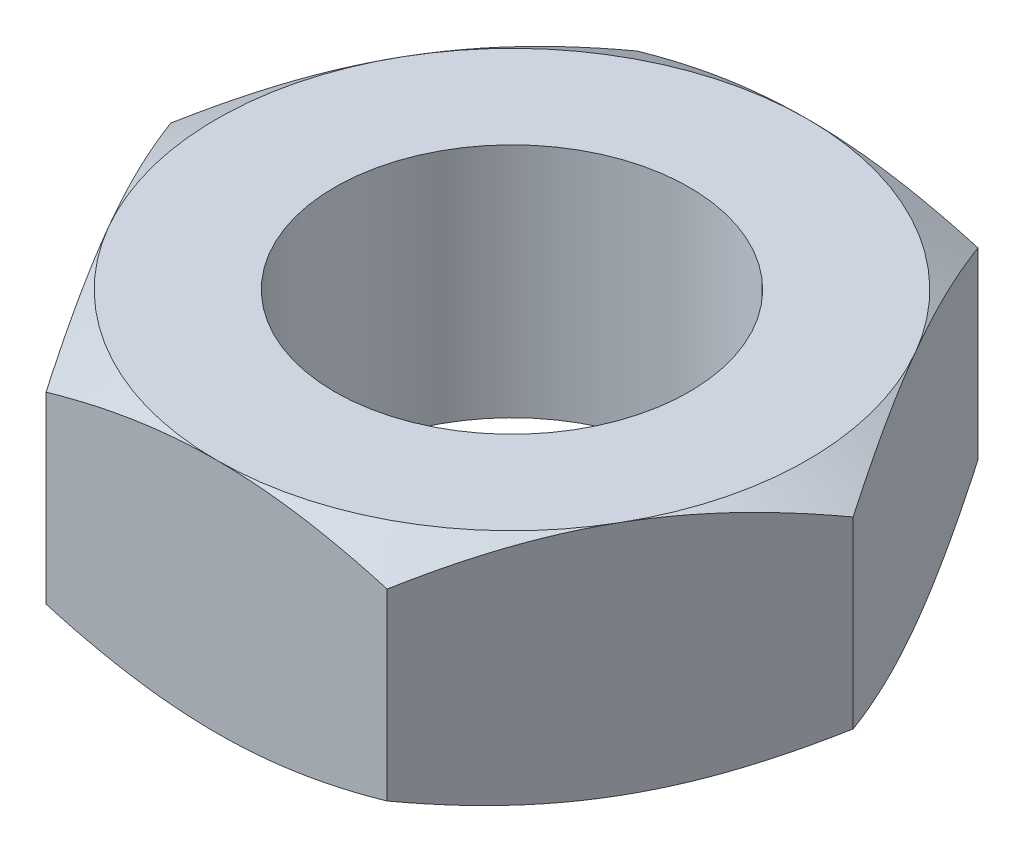
SolidWorks part; units mm, degrees
ref_plane "Front Plane" through (0, 0, 0) normal (0, 0, 1) x (1, 0, 0)
ref_plane "Top Plane" through (0, 0, 0) normal (0, 1, 0) x (1, 0, 0)
ref_plane "Right Plane" through (0, 0, 0) normal (1, 0, 0) x (0, 0, -1)
sketch "Sketch3" plane through (0, 0, 0) normal (0, 1, 0) x (1, 0, 0)
  line L1 (28.8675, 0) -> (14.4338, 25)
  line L2 (14.4338, 25) -> (-14.4338, 25)
  line L3 (-14.4338, 25) -> (-28.8675, 0)
  line L4 (-28.8675, 0) -> (-14.4338, -25)
  line L5 (-14.4338, -25) -> (14.4338, -25)
  line L6 (14.4338, -25) -> (28.8675, 0)
  circle A0 centre (0, 0) radius 15
  circle A1 centre (0, 0) radius 25 construction
  dimension "D1" = 50
  dimension "3" = 30
extrude "Boss-Extrude1" add sketch "Sketch3" along normal mid plane 20
sketch "Sketch4" plane through (0, -10, 0) normal (0, -1, 0) x (1, 0, 0)
  circle A0 centre (0, 0) radius 25
  dimension "D1" = 50
extrude "Cut-Extrude1" cut sketch "Sketch4" against normal blind 20 draft 60 flip side to cut
mirror "Mirror1" about plane through (0, 0, 0) normal (0, 1, 0) of "Cut-Extrude1"
